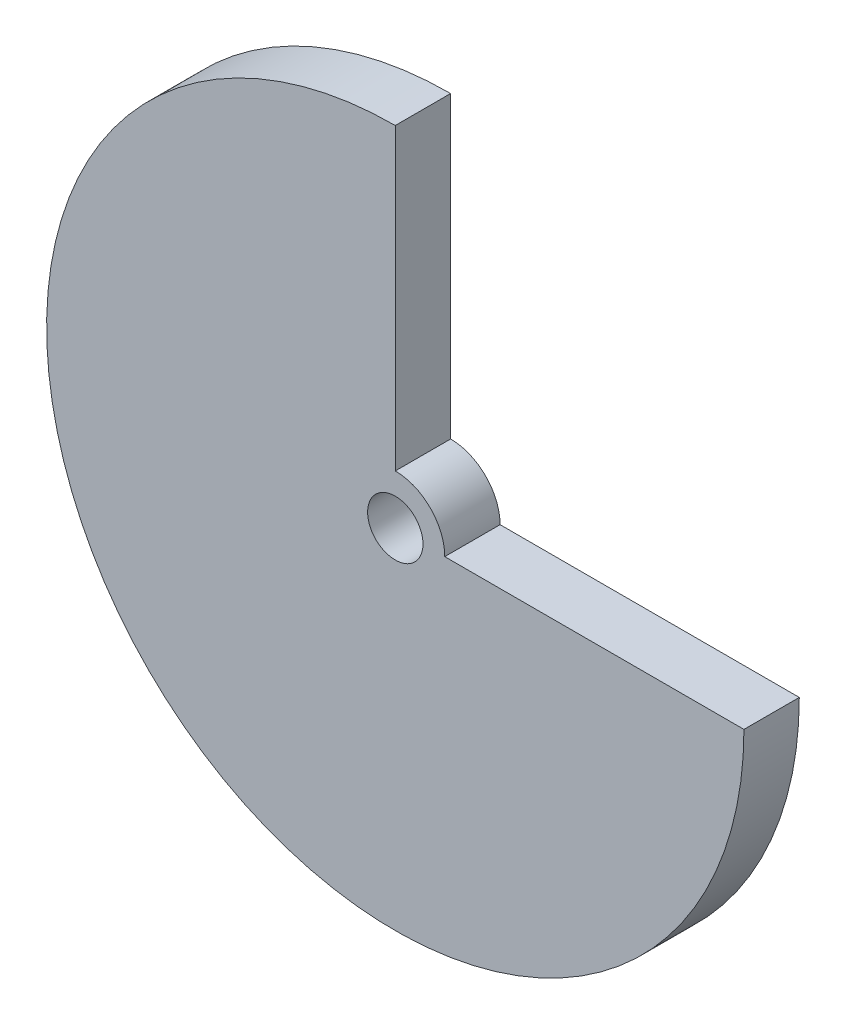
SolidWorks part; units mm, degrees
ref_plane "Front Plane" through (0, 0, 0) normal (0, 0, 1) x (1, 0, 0)
ref_plane "Top Plane" through (0, 0, 0) normal (0, 1, 0) x (1, 0, 0)
ref_plane "Right Plane" through (0, 0, 0) normal (1, 0, 0) x (0, 0, -1)
sketch "Sketch1" plane through (0, 0, 0) normal (0, 0, 1) x (1, 0, 0)
  line L1 (5.675, 0) -> (40, 0)
  line L2 (0, 5.675) -> (0, 40)
  arc A0 (0, 40) -> (40, 0) centre (0, 0) ccw
  arc A1 (5.675, 0) -> (0, 5.675) centre (0, 0) ccw
  dimension "D1" = 40
  dimension "D2" = 11.35
extrude "Boss-Extrude1" add sketch "Sketch1" along normal blind 6.35
sketch "Sketch2" plane through (0, 0, 6.35) normal (0, 0, 1) x (1, 0, 0)
  circle A0 centre (0, 0) radius 3.175
  dimension "D1" = 6.35
extrude "Cut-Extrude1" cut sketch "Sketch2" against normal through all both and the other way through all
equation "\"Wheel Thickness\"= 1in"
equation "\"Wheel Diameter\"= 3in"
equation "\"Motor Rear Diameter\" = 36.2mm"
equation "\"Motor Front Diameter\" = 12mm"
equation "\"Material Thickness\" = .25in"
equation "\"Wheel Cutout Diameter\"= 2cm"
equation "\"Motor Mount Tab Thickness\" = 100mm"
equation "\"Motor Mount Tab Height\" = 40mm"
equation "\"Motor Shaft Diameter\" = 3mm"
equation "\"Wheel Radius Clearance\" = 5mm"
equation "\"Wheel Cutout Width\" = 1.5in"
equation "\"Base Diameter\" = 10in"
equation "\"Wheel Mount Distance\" = 5mm"
equation "\"Motor Mount Distance\" = 50mm"
equation "\"Motor Cutout Length\" = 6in"
equation "\"Motor Cutout Height\" = 2in "
equation "\"Rod Diameter\" = 3/8in"
equation "\"Rod Length\" = 1.5in"
equation "\"Barrel Front Length\" = 1.8in"
equation "\"Barrerl Rear Length\" = 5in "
equation "\"Barrel Fillet Radius\" = 1in "
equation "\"Barrel Angle\" = 20deg"
equation "\"Barrel Diameter\" = 50mm"
equation "\"Barrel Shell Width\" = 2mm"
equation "\"Second Level Diameter\" = 10in"
equation "\"Ball Diameter\" = 40mm"
equation "\"Third Level Length\" = 9in"
equation "\"Third Level Height\" = 9in"
equation "\"Barrel Tab Clearance\" = 5mm"
equation "\"Barrel Tab Distance Away\" = 2mm"
equation "\"Hole Distance Apart\" = 2.8in"
equation "\"Barrel Tab Distance\"= 1.5in "
equation "\"Third Level Rod Distance\" = .5in"
equation " \"Second Rod Diameter\" = 3/8in"
equation "\"Second Rod Length\" = 3.88in"
equation "\"Bumper Wheel Clearance\" = 1.2in"
equation "\"Servo Tab Height\" = 4in"
equation "\"Servo Tab Width\" = 2in"
equation "\"Servo Tab Hole Horizontal Distance\" = 1in"
equation "\"Servo Tab Hole Vertical Distance\" = 1.5in "
equation "\"Servo Hole Vertical Distance\" = 3in"
equation "\"Servo Hole Diameter\" = 1/4in"
equation "\"D1@Boss-Extrude1\"=\"Material Thickness\""
equation "\"D1@Sketch1\"=\"Ball Diameter\""
equation "\"D2@Sketch1\"=\"Servo Hole Diameter\"+5mm"
equation "\"D1@Sketch2\"=\"Servo Hole Diameter\""
